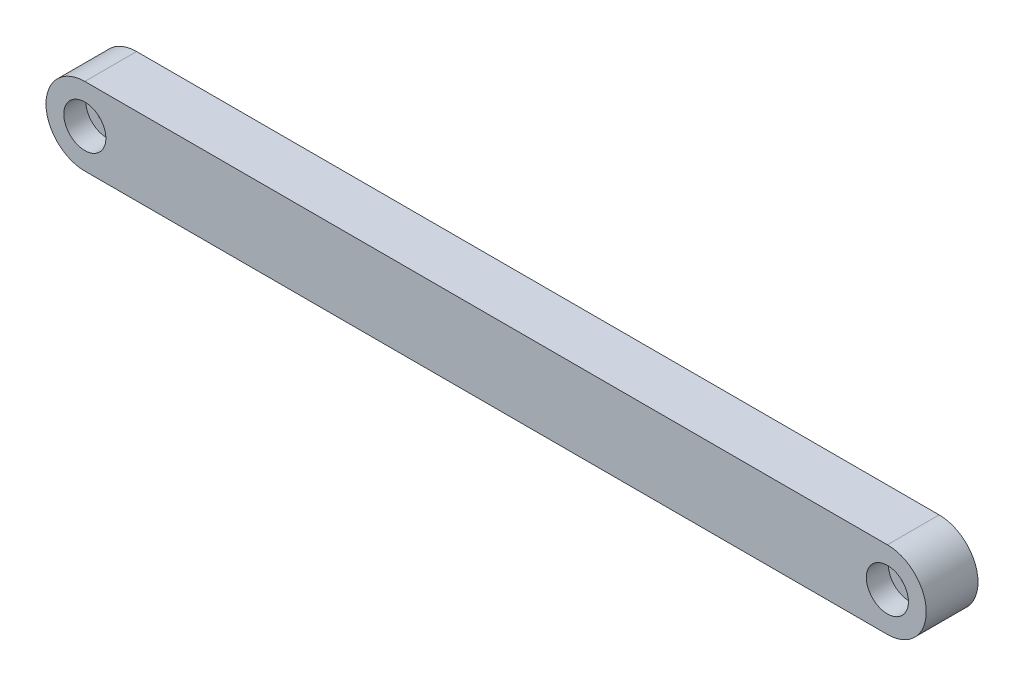
SolidWorks part; units mm, degrees
ref_plane "Top Plane" through (0, 0, 0) normal (0, 0, 1) x (1, 0, 0)
ref_plane "Right Plane" through (0, 0, 0) normal (0, 1, 0) x (1, 0, 0)
ref_plane "Front Plane" through (0, 0, 0) normal (1, 0, 0) x (0, 0, -1)
sketch "Sketch1" plane through (0, 0, 0) normal (0, 0, 1) x (1, 0, 0)
  line L0 (-62, 0) -> (62, 0) construction
  line L1 (-62, 6) -> (62, 6)
  line L2 (-62, -6) -> (62, -6)
  line L3 (0, 6) -> (0, -6) construction
  arc A0 (-62, 6) -> (-62, -6) centre (-62, 0) ccw
  arc A1 (62, -6) -> (62, 6) centre (62, 0) ccw
  circle A2 centre (-62, 0) radius 1.6 construction
  circle A3 centre (62, 0) radius 1.6 construction
  point P2 (0, 0)
  dimension "D1" = 3.2
  dimension "D2" = 124
  dimension "D3" = 12
extrude "Boss-Extrude1" add sketch "Sketch1" along normal blind 8
hole_wizard "CBORE for M3 Hex Socket Head Cap Screw1" positions "Sketch3" profile "Sketch4" counterbore size "M3" standard "ISO" end condition through all
sketch "Sketch3" plane through (0, 0, 8) normal (0, 0, 1) x (1, 0, 0)
  point P0 (-62, 0)
  point P3 (62, 0)
sketch "Sketch4" plane through (-62, 0, 8) normal (1, 0, 0) x (0, -1, 0)
  line L0 (0, 0) -> (0, 8)
  line L1 (0, 8) -> (1.6, 8)
  line L3 (1.6, 8) -> (1.6, 3.4)
  line L4 (1.6, 3.4) -> (3.25, 3.4)
  line L5 (3.25, 3.4) -> (3.25, 0)
  line L7 (3.25, 0) -> (0, 0)
  line L11 (0, -6.35) -> (0, 107.95) construction
  dimension "Thru Hole Dia." = 3.2
  dimension "Thru Hole Depth" = 8
  dimension "C'Bore Dia." = 6.5
  dimension "C'Bore Depth" = 3.4
